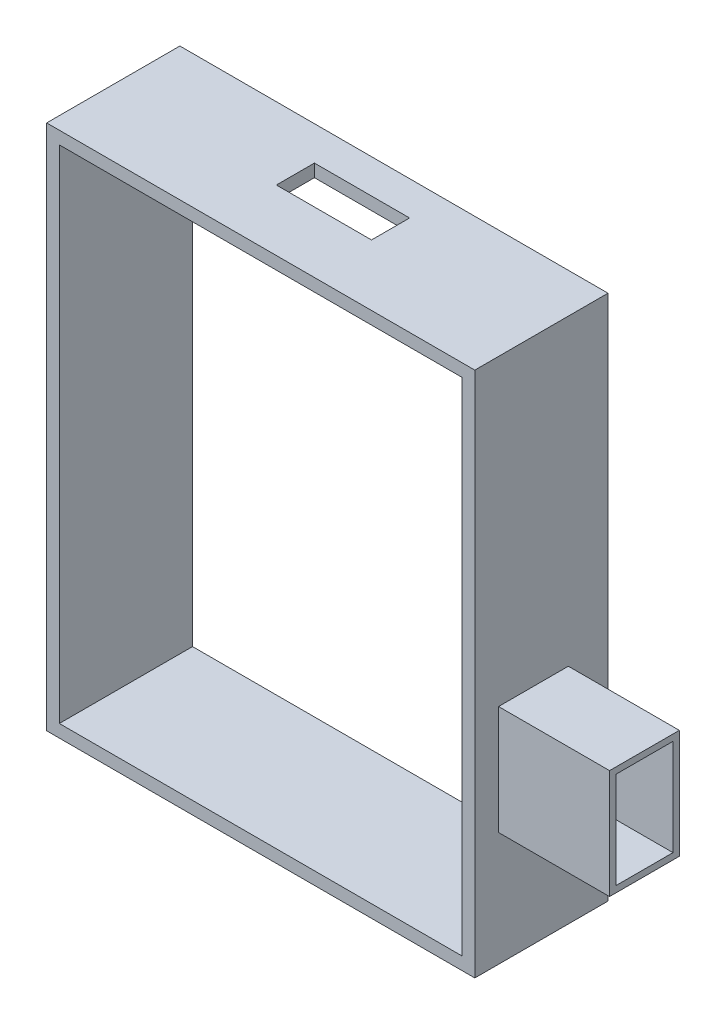
SolidWorks part; units mm, degrees
ref_plane "Front Plane" through (0, 0, 0) normal (0, 0, 1) x (1, 0, 0)
ref_plane "Top Plane" through (0, 0, 0) normal (0, 1, 0) x (1, 0, 0)
ref_plane "Right Plane" through (0, 0, 0) normal (1, 0, 0) x (0, 0, -1)
sketch "Sketch1" plane through (0, 0, 0) normal (0, 0, 1) x (1, 0, 0)
  line L0 (33.75, 41.5) -> (-33.75, 41.5)
  line L1 (31.75, 39.5) -> (-31.75, 39.5)
  line L2 (31.75, 39.5) -> (31.75, -39.5)
  line L3 (31.75, -39.5) -> (-31.75, -39.5)
  line L4 (-31.75, 39.5) -> (-31.75, -39.5)
  line L5 (31.75, 39.5) -> (-31.75, -39.5) construction
  line L6 (31.75, -39.5) -> (-31.75, 39.5) construction
  line L7 (-33.75, 41.5) -> (-33.75, -41.5)
  line L8 (33.75, -41.5) -> (-33.75, -41.5)
  line L9 (33.75, 41.5) -> (33.75, -41.5)
  point P0 (0, 0)
  dimension "D1" = 79
  dimension "D2" = 63.5
  dimension "D3" = 2
extrude "Boss-Extrude1" add sketch "Sketch1" along normal blind 21
sketch "Sketch2" plane through (33.75, 0, 0) normal (1, 0, 0) x (0, 0, -1)
  line L0 (-6.2546, -6.3071) -> (-17.2546, -6.3071)
  line L1 (-7.2546, -22.5071) -> (-16.2546, -22.5071)
  line L2 (-7.2546, -22.5071) -> (-7.2546, -7.3071)
  line L3 (-7.2546, -7.3071) -> (-16.2546, -7.3071)
  line L4 (-16.2546, -22.5071) -> (-16.2546, -7.3071)
  line L5 (-7.2546, -22.5071) -> (-16.2546, -7.3071) construction
  line L6 (-7.2546, -7.3071) -> (-16.2546, -22.5071) construction
  line L7 (-17.2546, -23.5071) -> (-17.2546, -6.3071)
  line L8 (-6.2546, -23.5071) -> (-17.2546, -23.5071)
  line L9 (-6.2546, -23.5071) -> (-6.2546, -6.3071)
  point P0 (-11.7546, -14.9071)
  point P5 (-11.4537, -13.7444)
  dimension "D1" = 15.2
  dimension "D2" = 9
  dimension "D3" = 1
extrude "Boss-Extrude2" add sketch "Sketch2" along normal blind 17.5
sketch "Sketch3" plane through (33.75, 0, 0) normal (1, 0, 0) x (0, 0, -1)
  line L2 (-7.2546, -22.5071) -> (-7.2546, -7.3071) construction
  line L3 (-16.2546, -22.5071) -> (-7.2546, -22.5071) construction
  line L4 (0, -41.5) -> (0, 41.5)
  line L5 (0, 41.5) -> (-21, 41.5)
  line L6 (-21, 41.5) -> (-21, -41.5)
  line L7 (-21, -41.5) -> (0, -41.5)
  line L8 (0, -41.5) -> (0, 41.5)
  line L9 (0, 41.5) -> (-21, 41.5)
  line L10 (-21, 41.5) -> (-21, -41.5)
  line L11 (-21, -41.5) -> (0, -41.5)
  line L15 (-7.2546, -7.3071) -> (-16.2546, -7.3071) construction
  line L16 (-16.2546, -7.3071) -> (-16.2546, -22.5071) construction
  line L17 (-7.2546, -22.5071) -> (-7.2546, -7.3071)
  line L18 (-16.2546, -22.5071) -> (-7.2546, -22.5071)
  line L22 (-7.2546, -7.3071) -> (-16.2546, -7.3071)
  line L23 (-16.2546, -7.3071) -> (-16.2546, -22.5071)
  dimension "D1" = 0
extrude "Cut-Extrude1" cut sketch "Sketch3" against normal blind 17 contours L22 L23 L18 L17
fillet "Fillet1" radius 1 1 edges at (31.75, -7.3071, 11.7546)
sketch "Sketch4" plane through (0, 41.5, 0) normal (0, 1, 0) x (1, 0, 0)
  line L1 (7.8395, -5.3731) -> (-7.1605, -5.3731)
  line L2 (7.8395, -5.3731) -> (7.8395, -11.3731)
  line L3 (7.8395, -11.3731) -> (-7.1605, -11.3731)
  line L4 (-7.1605, -5.3731) -> (-7.1605, -11.3731)
  line L5 (7.8395, -5.3731) -> (-7.1605, -11.3731) construction
  line L6 (7.8395, -11.3731) -> (-7.1605, -5.3731) construction
  point P0 (0.3395, -8.3731)
  dimension "D1" = 15
  dimension "D2" = 6
extrude "Cut-Extrude2" cut sketch "Sketch4" against normal blind 12
